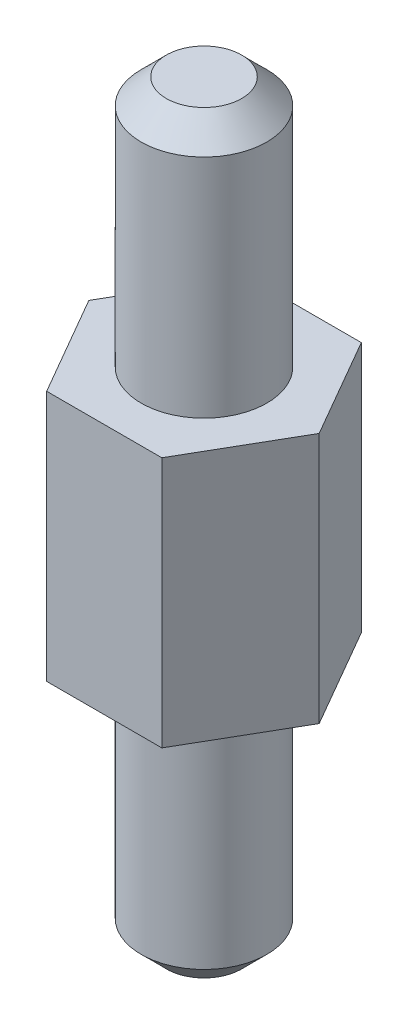
SolidWorks part; units mm, degrees
ref_plane "Front" through (0, 0, 0) normal (0, 0, 1) x (1, 0, 0)
ref_plane "Top" through (0, 0, 0) normal (0, 1, 0) x (1, 0, 0)
ref_plane "Right" through (0, 0, 0) normal (1, 0, 0) x (0, 0, -1)
sketch "Эскиз1" plane through (0, 0, 0) normal (0, 1, 0) x (1, 0, 0)
  line L0 (-2.75, 0) -> (2.75, 0) construction
  line L1 (-1.375, -2.3816) -> (1.375, 2.3816) construction
  line L2 (1.375, -2.3816) -> (-1.375, 2.3816) construction
  line L3 (-2.75, 0) -> (-1.375, 2.3816)
  line L4 (-1.375, 2.3816) -> (1.375, 2.3816)
  line L5 (1.375, 2.3816) -> (2.75, 0)
  line L6 (2.75, 0) -> (1.375, -2.3816)
  line L7 (1.375, -2.3816) -> (-1.375, -2.3816)
  line L8 (-1.375, -2.3816) -> (-2.75, 0)
  point P3 (0, 0)
  point P6 (0, 0)
  point P11 (0, 0)
  dimension "D1" = 5.5
  dimension "D2" = 5.5
  dimension "D3" = 5.5
  dimension "D4" = 60
  dimension "D5" = 60
extrude "Бобышка-Вытянуть1" add sketch "Эскиз1" along normal blind 6
sketch "Эскиз3" plane through (0, 6, 0) normal (0, 1, 0) x (1, 0, 0)
  circle A0 centre (0, 0) radius 1.5
  dimension "D1" = 3
extrude "Бобышка-Вытянуть2" add sketch "Эскиз3" along normal blind 6
sketch "Эскиз4" plane through (0, 0, 0) normal (0, -1, 0) x (1, 0, 0)
  circle A0 centre (0, 0) radius 1.5
  dimension "D1" = 3
extrude "Бобышка-Вытянуть3" add sketch "Эскиз4" along normal blind 6
chamfer "Фаска1" distance 0.6 angle 45 2 edges at (0, 12, 1.5) (0, -6, -1.5)
